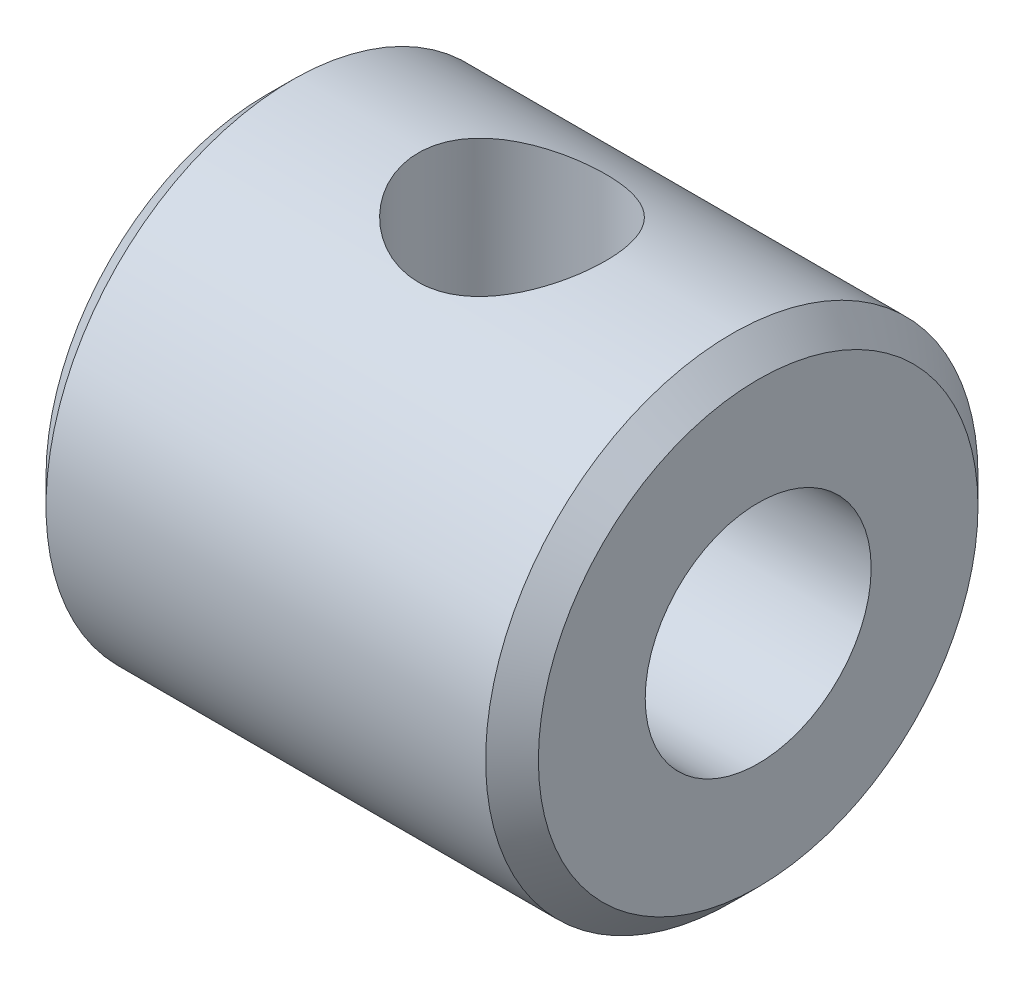
SolidWorks part; units mm, degrees
material "6061 Alloy"
ref_plane "Front Plane" through (0, 0, 0) normal (0, 0, 1) x (1, 0, 0)
ref_plane "Top Plane" through (0, 0, 0) normal (0, 1, 0) x (1, 0, 0)
ref_plane "Right Plane" through (0, 0, 0) normal (1, 0, 0) x (0, 0, -1)
sketch "Sketch1" plane through (0, 0, 0) normal (1, 0, 0) x (0, 0, -1)
  circle A0 centre (0, 0) radius 3.556
  dimension "D1" = 7.112
extrude "Boss-Extrude1" add sketch "Sketch1" along normal mid plane 7.112
hole_wizard "#30 (0.1285) Diameter Hole1" positions "Sketch2" profile "Sketch3" hole size "#30" standard "ANSI Inch" end condition through all
sketch "Sketch2" plane through (3.556, 0, 0) normal (1, 0, 0) x (0, 0, -1)
  point P0 (0, 0)
sketch "Sketch3" plane through (3.556, 0, 0) normal (0, 1, 0) x (0, 0, -1)
  line L0 (0, 0) -> (0, 7.112)
  line L1 (0, 7.112) -> (1.6319, 7.112)
  line L2 (1.6319, 7.112) -> (1.6319, 0)
  line L5 (1.6319, 0) -> (0, 0)
  line L11 (0, -6.35) -> (0, 107.95) construction
  dimension "Thru Hole Dia." = 3.2639
  dimension "Thru Hole Depth" = 7.112
chamfer "Chamfer2" distance 0.381 angle 45 2 edges at (-3.556, 0, -3.556) (3.556, 0, -3.556)
ref_plane "Plane1" through (0, 3.556, 0) normal (0, 1, 0) x (1, 0, 0)
hole_wizard "#65 (0.035) Diameter Hole2" positions "Sketch9" profile "Sketch10" hole size "#65" standard "ANSI Inch" end condition through all
sketch "Sketch9" plane through (0, 3.556, 0) normal (0, 1, 0) x (1, 0, 0)
  point P0 (0, 0)
sketch "Sketch10" plane through (0, 3.556, 0) normal (1, 0, 0) x (0, 0, 1)
  line L0 (0, 0) -> (0, 7.112)
  line L1 (0, 7.112) -> (0.4445, 7.112)
  line L2 (0.4445, 7.112) -> (0.4445, 0)
  line L5 (0.4445, 0) -> (0, 0)
  line L11 (0, -6.35) -> (0, 107.95) construction
  dimension "Thru Hole Dia." = 0.889
  dimension "Thru Hole Depth" = 7.112
hole_wizard "#6-32 Tapped Hole1" positions "Sketch11" profile "Sketch12" tap size "#6-32" standard "ANSI Inch"
sketch "Sketch11" plane through (0, 3.556, 0) normal (0, 1, 0) x (1, 0, 0)
  point P0 (0, 0)
sketch "Sketch12" plane through (0, 3.556, 0) normal (1, 0, 0) x (0, 0, 1)
  line L0 (0, 0) -> (0, 6.6039)
  line L1 (0, 6.6039) -> (1.3525, 5.7912)
  line L2 (1.3525, 5.7912) -> (1.3525, 0)
  line L5 (1.3525, 0) -> (0, 0)
  line L10 (0, 6.6039) -> (-1.3526, 5.7912) construction
  line L11 (0, -6.35) -> (0, 107.95) construction
  dimension "Tap Drill Dia." = 2.7051
  dimension "Tap Drill Depth" = 5.7912
  dimension "Drill Angle" = 118
cosmetic thread "Hole Thread1" parameters "D1"=2.8956, "D2"=3.5052
